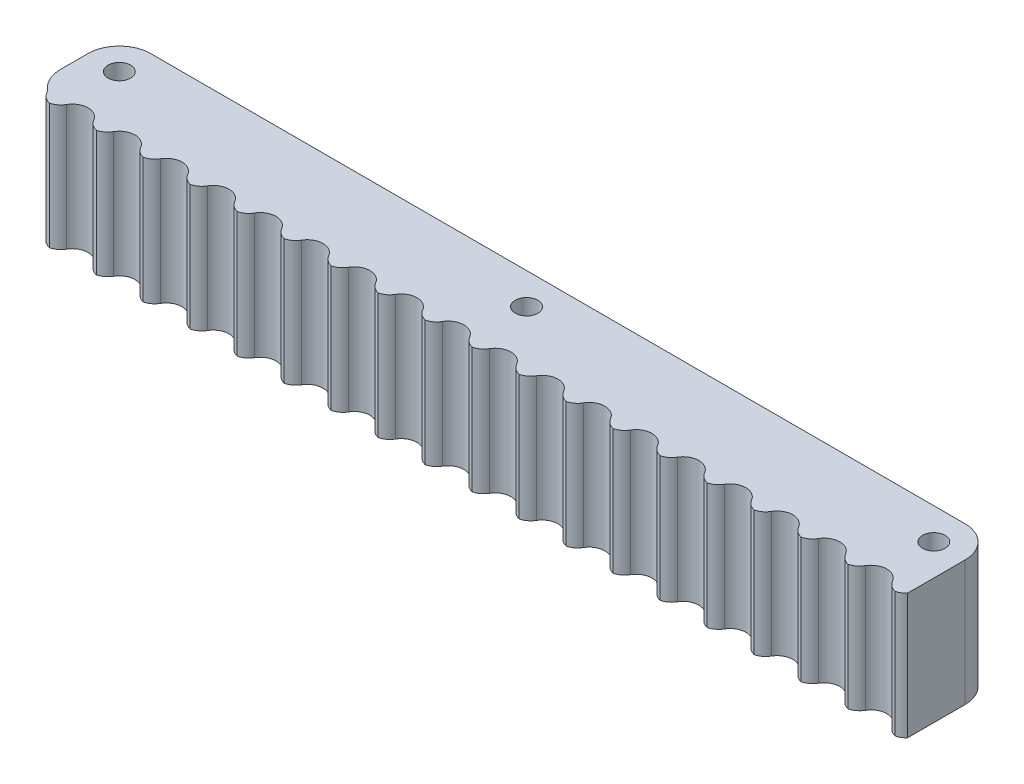
SolidWorks part; units mm, degrees
material "Rubber"
ref_plane "Front Plane" through (0, 0, 0) normal (0, 0, 1) x (1, 0, 0)
ref_plane "Top Plane" through (0, 0, 0) normal (0, 1, 0) x (1, 0, 0)
ref_plane "Right Plane" through (0, 0, 0) normal (1, 0, 0) x (0, 0, -1)
sketch "Sketch1" plane through (0, 0, 0) normal (0, 1, 0) x (1, 0, 0)
  line L1 (-70, -7.5) -> (70, -7.5)
  line L2 (-70, -7.5) -> (-70, 7.5)
  line L3 (-70, 7.5) -> (70, 7.5)
  line L4 (70, -7.5) -> (70, 7.5)
  line L5 (-70, -7.5) -> (70, 7.5) construction
  line L6 (-70, 7.5) -> (70, -7.5) construction
  point P0 (0, 0)
  dimension "D1" = 140
  dimension "D2" = 15
extrude "Boss-Extrude1" add sketch "Sketch1" along normal blind 20
sketch "Sketch2" plane through (0, 20, 0) normal (0, 1, 0) x (1, 0, 0)
  line L0 (-65, 2.5) -> (65, 2.5) construction
  line L1 (70, 7.5) -> (-70, 7.5) construction
  circle A0 centre (-65, 2.5) radius 1.8
  circle A1 centre (0, 2.5) radius 1.8
  circle A2 centre (65, 2.5) radius 1.8
  point P2 (0, 2.5)
  point P8 (-59.2982, 23.143)
  point P9 (0, 0)
  dimension "D2" = 3.6
  dimension "D1" = 130
  dimension "D3" = 5
extrude "Cut-Extrude1" cut sketch "Sketch2" against normal through all
fillet "Fillet1" radius 5 2 edges at (70, 10, -7.5) (-70, 10, -7.5)
sketch "Sketch3" plane through (0, 20, 0) normal (0, 1, 0) x (1, 0, 0)
  line L0 (-70, -7.5) -> (70, -7.5) construction
  line L1 (-72.5, -7.5) -> (-74.3301, -7.5) construction
  line L3 (-72.5, -7.5) -> (-67.5, -7.5) construction
  line L4 (-67.5, -7.5) -> (-65.6699, -7.5) construction
  arc A0 (-67.8349, -6.25) -> (-72.1651, -6.25) centre (-70, -7.5) ccw
  arc A1 (-72.5, -7.5) -> (-67.5, -7.5) centre (-70, -7.5) ccw construction
  arc A2 (-67.8349, -6.25) -> (-65.6699, -7.5) centre (-65.6699, -5) ccw
  arc A3 (-72.1651, -6.25) -> (-74.3301, -7.5) centre (-74.3301, -5) cw
  arc A4 (-74.3301, -7.5) -> (-65.6699, -7.5) centre (-70, -7.5) ccw
  point P5 (-79.6398, -10)
  point P8 (-70, -7.5)
  point P9 (-70, -7.5)
  point P16 (-75, -10.5859)
  point P17 (0, 0)
  point P18 (-69.3254, -10)
  point P19 (-75, -9.9569)
  dimension "D1" = 5
  dimension "D2" = 2.5
extrude "Cut-Extrude2" cut sketch "Sketch3" against normal through all
pattern_linear "LPattern1" count 42 spacing 7.5 along (1, 0, 0) of "Cut-Extrude2"
fillet "Fillet2" radius 5 1 edges at (-70, 10, 5)
